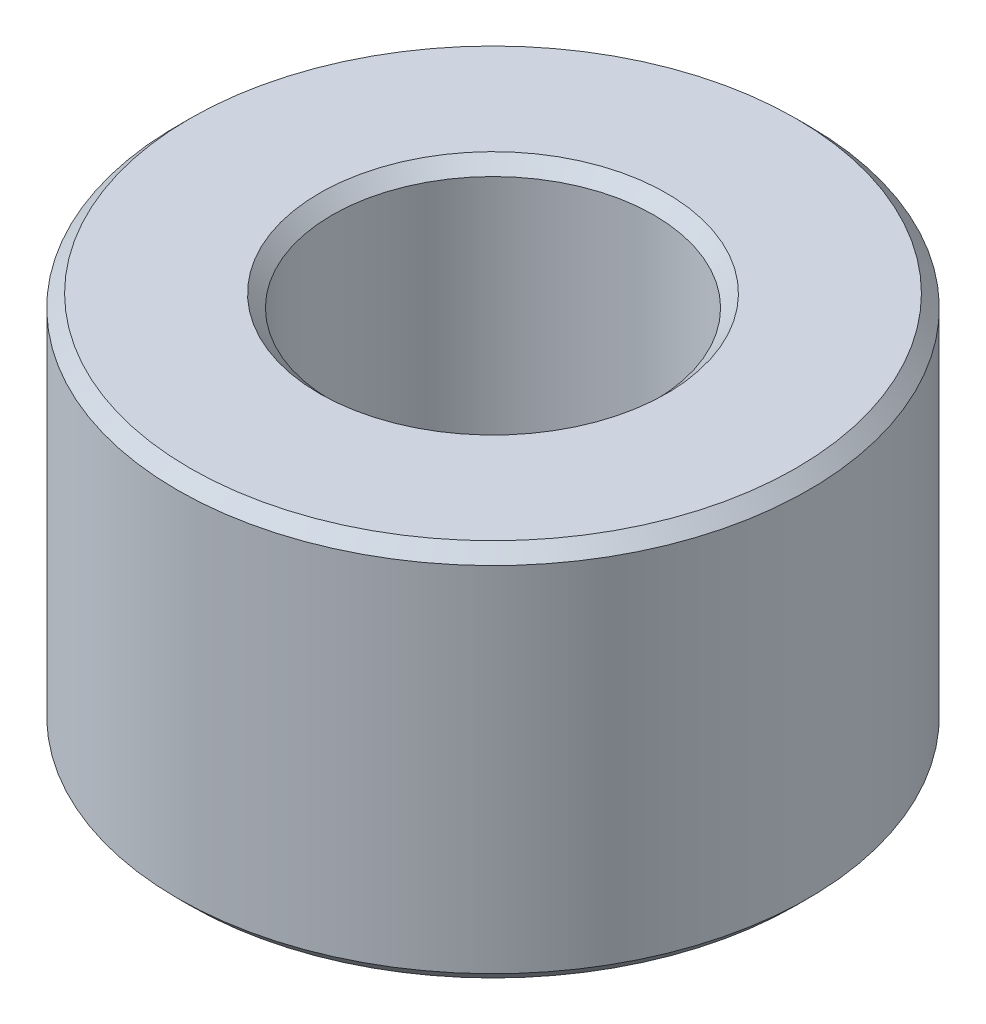
SolidWorks part; units mm, degrees
material "6061-T6 (SS)"
ref_plane "Front Plane" through (0, 0, 0) normal (0, 0, 1) x (1, 0, 0)
ref_plane "Top Plane" through (0, 0, 0) normal (0, 1, 0) x (1, 0, 0)
ref_plane "Right Plane" through (0, 0, 0) normal (1, 0, 0) x (0, 0, -1)
sketch "Sketch1" plane through (0, 0, 0) normal (1, 0, 0) x (0, 0, -1)
  line L0 (0, 2.1339) -> (0, -2.1339) construction
  line L1 (2.55, 2.8) -> (2.75, 3)
  line L2 (2.75, 3) -> (4.8, 3)
  line L3 (2.55, 2.8) -> (2.55, -2.8)
  line L4 (2.75, -3) -> (4.8, -3)
  line L5 (5, 2.8) -> (5, -2.8)
  line L6 (2.55, 3) -> (5, -3) construction
  line L7 (2.55, -3) -> (5, 3) construction
  line L8 (4.8, 3) -> (5, 2.8)
  line L9 (4.8, -3) -> (5, -2.8)
  line L10 (2.55, -2.8) -> (2.75, -3)
  point P0 (3.775, 0)
  point P4 (0, 0)
  dimension "D1" = 2.45
  dimension "D2" = 6
  dimension "D3" = 2.55
revolve "Revolve1" add sketch "Sketch1" angle 360 about L0
